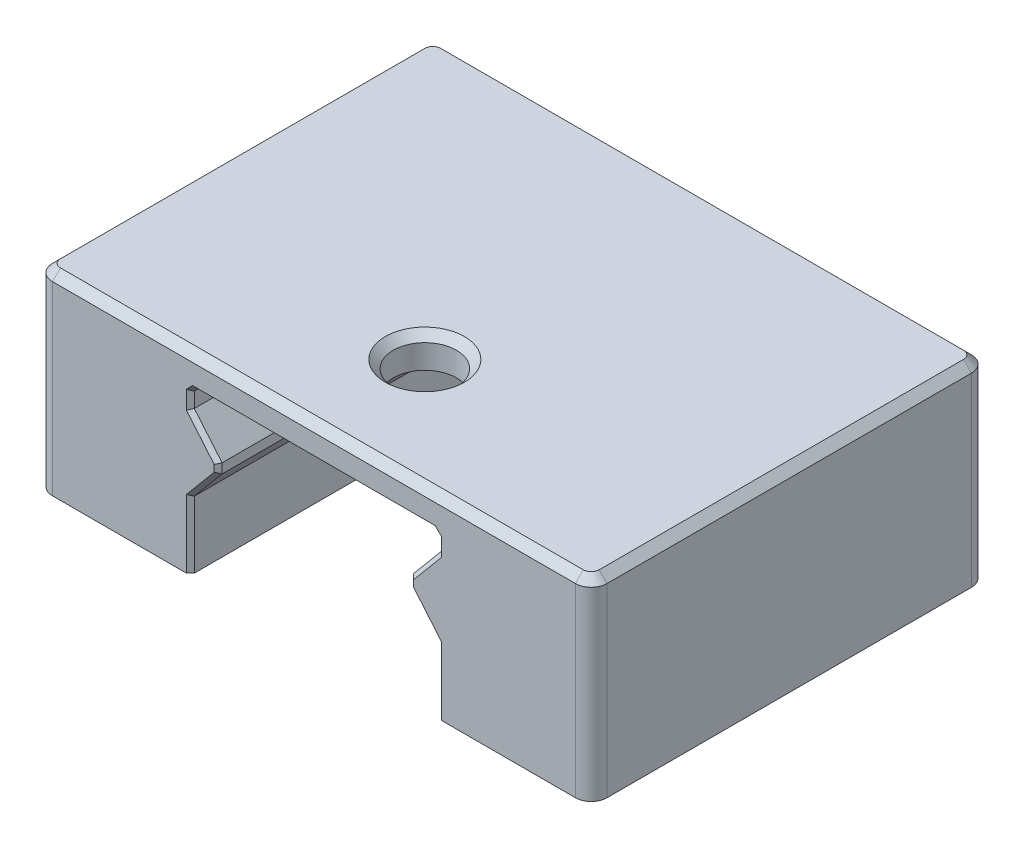
SolidWorks part; units mm, degrees
material "PET"
ref_plane "Přední rovina" through (0, 0, 0) normal (0, 0, 1) x (1, 0, 0)
ref_plane "Horní rovina" through (0, 0, 0) normal (0, 1, 0) x (1, 0, 0)
ref_plane "Pravá rovina" through (0, 0, 0) normal (1, 0, 0) x (0, 0, -1)
sketch "Skica1" plane through (0, 0, 0) normal (0, 0, 1) x (1, 0, 0)
  line L0 (17.5, 8) -> (17.5, 0) construction
  line L2 (0, 0) -> (0, 8)
  line L3 (0, 8) -> (35, 8)
  line L4 (35, 0) -> (35, 8)
  line L5 (0, 0) -> (35, 8) construction
  line L6 (0, 8) -> (35, 0) construction
  line L7 (9.7, 0) -> (11.4537, 2.09)
  line L8 (11.4537, 2.09) -> (11.4537, 2.7)
  line L9 (11.4537, 2.7) -> (9.7, 4.79)
  line L10 (9.7, 4.79) -> (9.7, 5.74)
  line L11 (9.95, 5.99) -> (25.05, 5.99)
  line L12 (9.7, 5.74) -> (9.95, 5.99)
  line L13 (25.3, 5.74) -> (25.05, 5.99)
  line L14 (25.3, 4.79) -> (25.3, 5.74)
  line L15 (23.5463, 2.7) -> (25.3, 4.79)
  line L16 (23.5463, 2.09) -> (23.5463, 2.7)
  line L17 (25.3, 0) -> (23.5463, 2.09)
  line L19 (0, 0) -> (0, -4.21)
  line L20 (0, -4.21) -> (9.7, -4.21)
  line L21 (9.7, -4.21) -> (9.7, 0)
  line L22 (25.3, 0) -> (25.3, -4.21)
  line L23 (25.3, -4.21) -> (35, -4.21)
  line L24 (35, -4.21) -> (35, 0)
  point P4 (17.5, 4)
  point P13 (9.7, 5.99)
  point P18 (17.5, 5.99)
  dimension "D1" = 35
  dimension "D2" = 8
  dimension "D3" = 15.6
  dimension "D4" = 4.21
  dimension "D5" = 15.6
  dimension "D7" = 3.29
  dimension "D8" = 50
  dimension "D9" = 0.61
  dimension "D10" = 4.21
extrude "Přidat vysunutím1" add sketch "Skica1" along normal blind 25
sketch "Skica2" plane through (0, 8, 0) normal (0, 1, 0) x (1, 0, 0)
  line L0 (17.5, 0) -> (17.5, -25) construction
  line L1 (35, 0) -> (0, 0) construction
  line L2 (35, -25) -> (0, -25) construction
  circle A0 centre (17.5, -18) radius 2
  dimension "D1" = 7
  dimension "D2" = 4
extrude "Odebrat vysunutím1" cut sketch "Skica2" against normal up to surface (2.01 mm away) up to face at (17.5, 5.99, 12.5)
fillet "Zaoblit1" radius 1 4 edges at (0, 1.895, 25) (35, 1.895, 25) (35, 1.895, 0) (0, 1.895, 0)
chamfer "Zkosení4" distance 0.25 angle 45 26 edges at (9.7, -2.105, 25) (10.5769, 1.045, 25) (11.4537, 2.395, 25) (25.3, -2.105, 25) (24.4231, 1.045, 25) (23.5463, 2.395, 25) (24.4231, 3.745, 25) (25.3, 5.265, 25) (25.175, 5.865, 25) (17.5, 5.99, 25) (9.825, 5.865, 25) (9.7, 5.265, 25) (10.5769, 3.745, 25) (25.3, -2.105, 0) (24.4231, 1.045, 0) (23.5463, 2.395, 0) (24.4231, 3.745, 0) (9.7, -2.105, 0) (10.5769, 1.045, 0) (11.4537, 2.395, 0) (10.5769, 3.745, 0) (9.7, 5.265, 0) (9.825, 5.865, 0) (17.5, 5.99, 0) (25.175, 5.865, 0) (25.3, 5.265, 0)
chamfer "Zkosení5" distance 0.5 angle 45 8 edges at (17.5, 8, 25) (34.7071, 8, 24.7071) (0.2929, 8, 24.7071) (35, 8, 12.5) (0, 8, 12.5) (34.7071, 8, 0.2929) (0.2929, 8, 0.2929) (17.5, 8, 0)
chamfer "Zkosení6" distance 0.5 angle 45 1 edges at (15.5, 8, 18)
